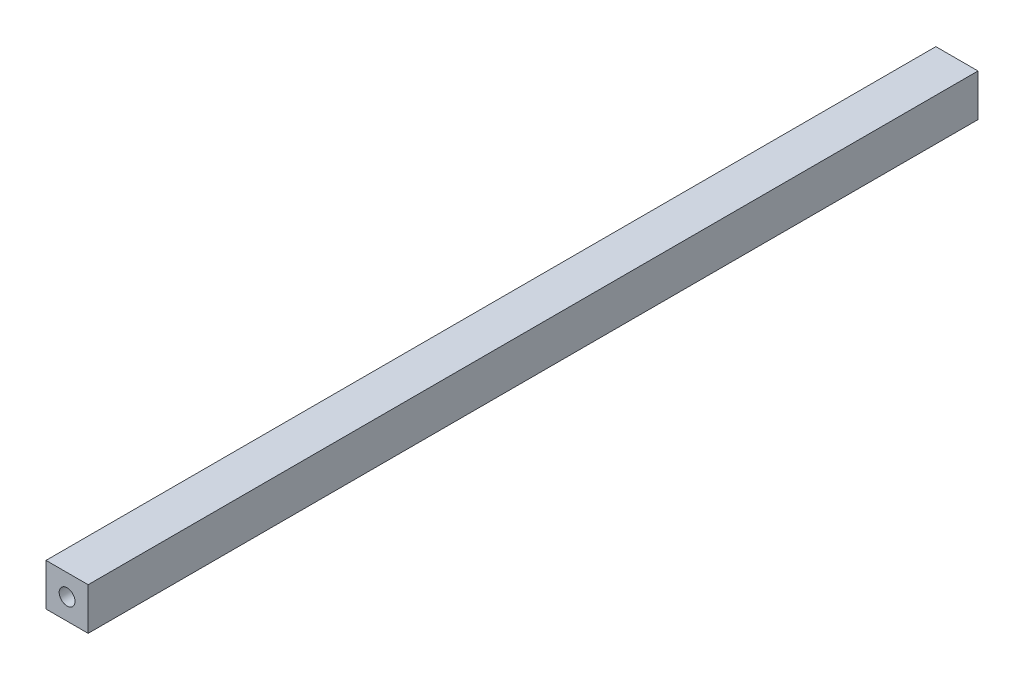
SolidWorks part; units mm, degrees
ref_plane "Front Plane" through (0, 0, 0) normal (0, 0, 1) x (1, 0, 0)
ref_plane "Top Plane" through (0, 0, 0) normal (0, 1, 0) x (1, 0, 0)
ref_plane "Right Plane" through (0, 0, 0) normal (1, 0, 0) x (0, 0, -1)
sketch "Sketch1" plane through (0, 0, 0) normal (0, 0, 1) x (1, 0, 0)
  line L1 (0, 0) -> (25.4, 0)
  line L2 (0, 0) -> (0, 25.4)
  line L3 (0, 25.4) -> (25.4, 25.4)
  line L4 (25.4, 0) -> (25.4, 25.4)
  dimension "D1" = 25.4
  dimension "D2" = 25.4
extrude "Boss-Extrude1" add sketch "Sketch1" along normal blind 536.194
sketch "Sketch2" plane through (0, 0, 536.194) normal (0, 0, 1) x (1, 0, 0)
  line L0 (0, 25.4) -> (0, 0) construction
  line L2 (25.4, 25.4) -> (0, 25.4) construction
  point P0 (12.7, 12.7)
  dimension "D1" = 12.7
  dimension "D2" = 12.7
sketch "Sketch3" plane through (0, 0, 0) normal (0, 0, -1) x (-1, 0, 0)
  line L0 (-25.4, 25.4) -> (0, 25.4) construction
  line L1 (0, 25.4) -> (0, 0) construction
  point P0 (-12.7, 12.7)
  dimension "D1" = 12.7
  dimension "D2" = 12.7
hole_wizard "3/8 (0.375) Diameter Hole1" positions "Sketch7" profile "Sketch8" hole size "3/8" standard "ANSI Inch"
sketch "Sketch7" plane through (0, 0, 0) normal (0, 0, -1) x (-1, 0, 0)
  point P0 (-12.7, 12.7)
sketch "Sketch8" plane through (12.7, 12.7, 0) normal (1, 0, 0) x (0, 1, 0)
  line L0 (0, 0) -> (0, 28.2616)
  line L1 (0, 28.2616) -> (4.7625, 25.4)
  line L2 (4.7625, 25.4) -> (4.7625, 0)
  line L5 (4.7625, 0) -> (0, 0)
  line L10 (0, 28.2616) -> (-4.7625, 25.4) construction
  line L11 (0, -6.35) -> (0, 107.95) construction
  dimension "Hole Dia." = 9.525
  dimension "Hole Depth" = 25.4
  dimension "Drill Angle" = 118
hole_wizard "3/8 (0.375) Diameter Hole2" positions "Sketch10" profile "Sketch9" hole size "3/8" standard "ANSI Inch"
sketch "Sketch10" plane through (0, 0, 536.194) normal (0, 0, 1) x (1, 0, 0)
  point P0 (12.7, 12.7)
sketch "Sketch9" plane through (12.7, 12.7, 536.194) normal (1, 0, 0) x (0, -1, 0)
  line L0 (0, 0) -> (0, 28.2616)
  line L1 (0, 28.2616) -> (4.7625, 25.4)
  line L2 (4.7625, 25.4) -> (4.7625, 0)
  line L5 (4.7625, 0) -> (0, 0)
  line L10 (0, 28.2616) -> (-4.7625, 25.4) construction
  line L11 (0, -6.35) -> (0, 107.95) construction
  dimension "Hole Dia." = 9.525
  dimension "Hole Depth" = 25.4
  dimension "Drill Angle" = 118
equation "\"D2@Sketch1\"=\"D1@Sketch1\""
